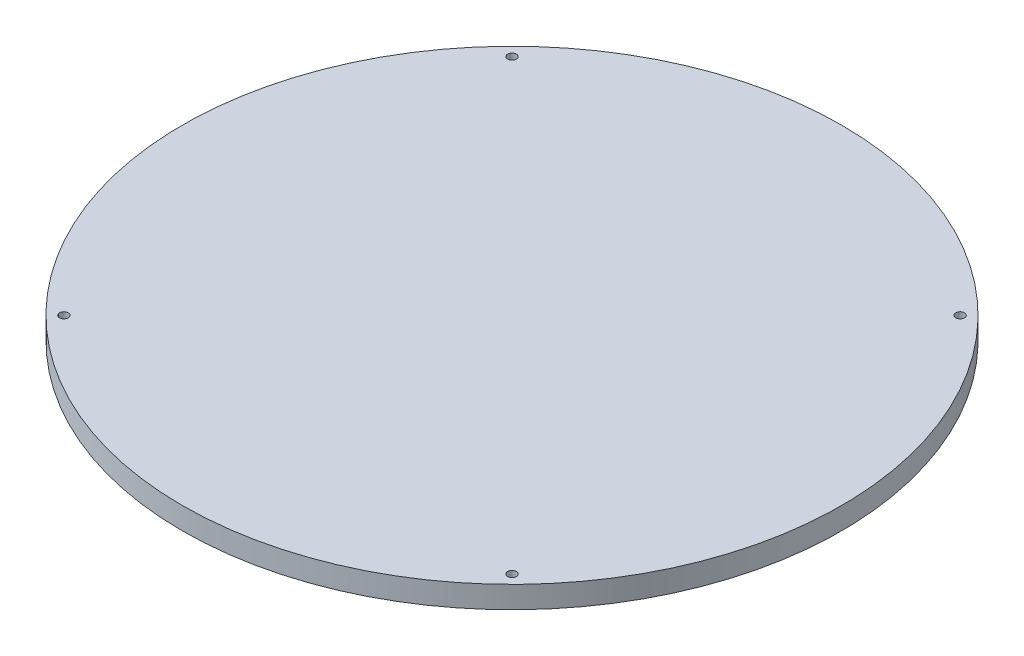
SolidWorks part; units mm, degrees
material "1060 Alloy"
ref_plane "Front Plane" through (0, 0, 0) normal (0, 0, 1) x (1, 0, 0)
ref_plane "Top Plane" through (0, 0, 0) normal (0, 1, 0) x (1, 0, 0)
ref_plane "Right Plane" through (0, 0, 0) normal (1, 0, 0) x (0, 0, -1)
sketch "Sketch1" plane through (0, 0, 0) normal (0, 1, 0) x (1, 0, 0)
  circle A0 centre (0, 0) radius 150
extrude "Boss-Extrude1" add sketch "Sketch1" along normal blind 10
sketch "Sketch2" plane through (0, 10, 0) normal (0, 1, 0) x (1, 0, 0)
  line L2 (0, 0) -> (115.5258, 115.5258) construction
  circle A16 centre (101.9745, 101.9745) radius 2
  circle A17 centre (101.9745, -101.9745) radius 2
  circle A18 centre (-101.9745, -101.9745) radius 2
  circle A19 centre (-101.9745, 101.9745) radius 2
  point P39 (0, 0)
  point P49 (0, 0)
  dimension "D5" = 4
extrude "Cut-Extrude1" cut sketch "Sketch2" against normal blind 10
